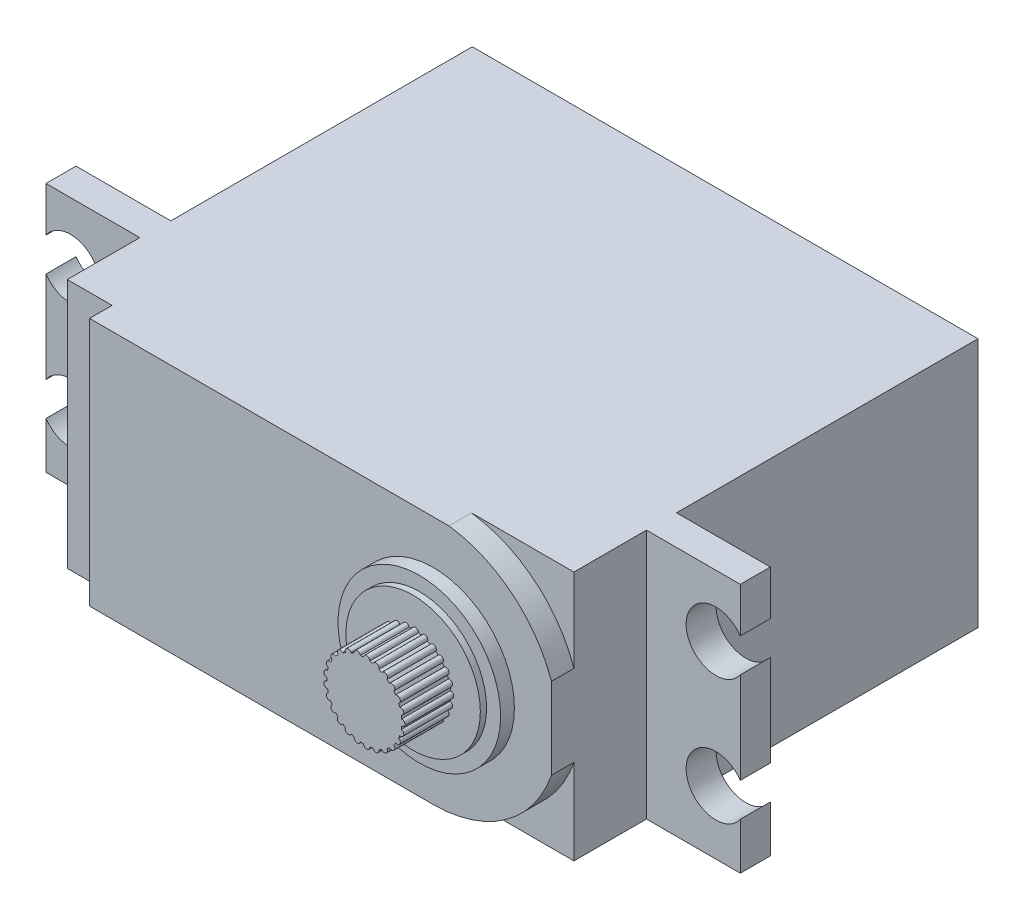
SolidWorks part; units mm, degrees
ref_plane "Ebene vorne" through (0, 0, 0) normal (0, 0, 1) x (1, 0, 0)
ref_plane "Ebene oben" through (0, 0, 0) normal (0, 1, 0) x (1, 0, 0)
ref_plane "Ebene rechts" through (0, 0, 0) normal (1, 0, 0) x (0, 0, -1)
sketch "Skizze1" plane through (0, 0, 0) normal (0, 0, 1) x (1, 0, 0)
  line L1 (0, 0) -> (55.5, 0)
  line L3 (0, -20) -> (55.5, -20)
  line L6 (0, 0) -> (62.9926, 0) construction
  line L7 (62.9926, 0) -> (27.75, 0) construction
  line L8 (27.75, 0) -> (27.75, 17.3109) construction
  line L9 (27.75, 17.3109) -> (27.75, -28.9374) construction
  line L12 (0, 0) -> (55.5, 0) construction
  line L13 (0, -3.5735) -> (0, 0) construction
  line L14 (0, 0) -> (55.5, 0) construction
  line L15 (55.5, 0) -> (55.5, -3.5735) construction
  line L16 (0, -16.266) -> (0, -20) construction
  line L17 (55.5, -6.266) -> (55.5, -13.5735) construction
  line L18 (0, -16.266) -> (0, -20)
  line L19 (0, -6.266) -> (0, -13.5735) construction
  line L20 (0, -3.5735) -> (0, 0)
  line L21 (55.5, 0) -> (55.5, -3.5735)
  line L22 (55.5, -6.266) -> (55.5, -13.5735)
  line L23 (0, -6.266) -> (0, -13.5735)
  line L24 (55.5, -16.266) -> (55.5, -20) construction
  line L25 (55.5, -16.266) -> (55.5, -20)
  arc A0 (0, -6.266) -> (0, -3.5735) centre (1.9566, -4.9197) ccw
  arc A4 (55.5, -6.266) -> (55.5, -3.5735) centre (53.5434, -4.9197) cw
  arc A5 (0, -16.266) -> (0, -13.5735) centre (1.9566, -14.9197) ccw
  arc A6 (55.5, -16.266) -> (55.5, -13.5735) centre (53.5434, -14.9197) cw
  dimension "D3" = 4.75
  dimension "D4" = 4.75
  dimension "D1" = 55.5
  dimension "D2" = 20
  dimension "D5" = 10
extrude "Aufsatz-Linear austragen1" add sketch "Skizze1" along normal blind 2.4
sketch "Skizze3" plane through (0, 0, 2.4) normal (0, 0, 1) x (1, 0, 0)
  line L0 (55.5, 0) -> (0, 0) construction
  line L1 (7.5, 0) -> (48, 0)
  line L2 (7.5, 0) -> (7.5, -20)
  line L3 (7.5, -20) -> (48, -20)
  line L4 (48, 0) -> (48, -20)
  line L5 (0, -20) -> (55.5, -20) construction
  dimension "D1" = 40.5
  dimension "D2" = 7.5
extrude "Aufsatz-Linear austragen2" add sketch "Skizze3" along normal blind 5.8
sketch "Skizze4" plane through (0, 0, 8.2) normal (0, 0, 1) x (1, 0, 0)
  line L0 (0, 0) -> (55.5, 0) construction
  line L1 (55.5, 0) -> (53.5434, -4.9197) construction
  line L2 (53.5434, -4.9197) -> (1.9566, -4.9197) construction
  line L4 (55.5, -13.5735) -> (55.5, -6.266) construction
  line L5 (55.5, -9.9197) -> (0, -9.9197) construction
  line L6 (0, -6.266) -> (0, -13.5735) construction
  line L7 (11.0819, 0) -> (38.5434, 0)
  line L8 (11.0819, 0) -> (11.0819, -19.9197)
  line L9 (11.0819, -19.9197) -> (38.5434, -19.9197)
  arc A0 (38.5434, -19.9197) -> (37.279, 0) centre (38.5434, -9.9197) ccw
  line M4 (48, -20) -> (48, 0)
  line M5 (48, 0) -> (7.5, 0)
  dimension "D1" = 20
  dimension "D2" = 15
extrude "Aufsatz-Linear austragen3" add sketch "Skizze4" along normal blind 1.8 contours A0 L7 L8 L9 M4 M5
sketch "Skizze5" plane through (0, 0, 10) normal (0, 0, 1) x (1, 0, 0)
  line L0 (0, 0) -> (55.5, 0) construction
  line L1 (0, -10) -> (38.5434, -10) construction
  line L2 (55.5, -20) -> (0, -20) construction
  line L3 (0, -20) -> (0, 0) construction
  line L4 (0, 0) -> (0, -10) construction
  line L5 (38.5434, -10) -> (55.5, -10) construction
  line L7 (53.5434, -4.9197) -> (38.5434, -4.9197) construction
  line L10 (38.5434, -9.9197) -> (38.5434, 2.8497) construction
  line L11 (38.5434, 2.8497) -> (38.5434, -23.2481) construction
  circle A0 centre (38.5434, -10) radius 6.5
  dimension "D1" = 13
extrude "Aufsatz-Linear austragen4" add sketch "Skizze5" along normal blind 1.1
sketch "Skizze7" plane through (0, 0, 11.1) normal (0, 0, 1) x (1, 0, 0)
  line L0 (48, 0) -> (48, -9.9197) construction
  line L1 (48, -13.1714) -> (48, -6.6681) construction
  line L2 (48, -9.9197) -> (0, -9.9197) construction
  line L3 (0, -6.266) -> (0, -13.5735) construction
  line L4 (48, -5.4374) -> (53.5434, -4.9197) construction
  line L5 (53.5434, -4.9197) -> (1.9566, -4.9197) construction
  line L6 (38.5434, -10) -> (38.5434, -22.4105) construction
  line L7 (38.5434, -22.4105) -> (38.5434, 3.8865) construction
  circle A0 centre (38.5434, -10) radius 5.375
  dimension "D1" = 10.75
extrude "Aufsatz-Linear austragen6" add sketch "Skizze7" along normal blind 0.5
sketch "Skizze8" plane through (0, 0, 11.6) normal (0, 0, 1) x (1, 0, 0)
  line L0 (55.5, 0) -> (55.5, -20) construction
  line L1 (55.5, -20) -> (55.5, -10) construction
  line L2 (55.5, -10) -> (41.7931, -9.9876) construction
  line L3 (11.0819, 0) -> (11.0819, -19.9197) construction
  line L4 (38.5434, -13) -> (38.5434, -21.6578) construction
  line L5 (53.5434, -4.9197) -> (11.0819, -4.9197) construction
  line L6 (38.5434, -21.6578) -> (38.5434, -13) construction
  line L7 (38.5434, -7) -> (38.5434, 1.1553) construction
  line L8 (35.5435, -9.982) -> (11.0819, -9.9599) construction
  line L9 (41.2938, -9.9872) -> (38.5434, -9.9847) construction
  arc A0 (41.377, -10.9854) -> (41.5012, -10.5015) centre (41.4492, -10.7461) ccw
  arc A1 (35.5461, -9.8731) -> (35.5461, -10.1269) centre (38.5434, -10) ccw
  arc A2 (41.533, -10.2498) -> (41.533, -9.7502) centre (41.5434, -10) ccw
  arc A3 (41.0429, -11.6591) -> (41.2836, -11.2214) centre (41.1724, -11.4453) ccw
  arc A4 (40.5518, -12.2286) -> (40.8937, -11.8644) centre (40.7303, -12.0536) ccw
  arc A5 (39.9344, -12.658) -> (40.3562, -12.3903) centre (40.1509, -12.533) ccw
  arc A6 (39.2297, -12.9204) -> (39.7048, -12.7661) centre (39.4705, -12.8532) ccw
  arc A7 (38.4819, -12.9994) -> (38.9804, -12.968) centre (38.7318, -12.9941) ccw
  arc A8 (37.7379, -12.8898) -> (38.2286, -12.9834) centre (37.9813, -12.9469) ccw
  arc A9 (37.0445, -12.5987) -> (37.4965, -12.8114) centre (37.2661, -12.7145) ccw
  arc A10 (36.4453, -12.1443) -> (36.8303, -12.4627) centre (36.6312, -12.3115) ccw
  arc A11 (35.978, -11.5552) -> (36.2716, -11.9593) centre (36.1164, -11.7634) ccw
  arc A12 (35.6718, -10.8683) -> (35.8557, -11.3328) centre (35.7541, -11.1044) ccw
  arc A13 (35.5461, -10.1269) -> (35.6087, -10.6225) centre (35.5671, -10.376) ccw
  arc A14 (35.6087, -9.3775) -> (35.5461, -9.8731) centre (35.5671, -9.624) ccw
  arc A15 (35.8557, -8.6672) -> (35.6718, -9.1317) centre (35.7541, -8.8956) ccw
  arc A16 (36.2716, -8.0407) -> (35.978, -8.4448) centre (36.1164, -8.2366) ccw
  arc A17 (36.8303, -7.5373) -> (36.4453, -7.8557) centre (36.6312, -7.6885) ccw
  arc A18 (37.4965, -7.1886) -> (37.0445, -7.4013) centre (37.2661, -7.2855) ccw
  arc A19 (38.2286, -7.0166) -> (37.7379, -7.1102) centre (37.9813, -7.0531) ccw
  arc A20 (38.9804, -7.032) -> (38.4819, -7.0006) centre (38.7318, -7.0059) ccw
  arc A21 (39.7048, -7.2339) -> (39.2297, -7.0796) centre (39.4705, -7.1468) ccw
  arc A22 (40.3562, -7.6097) -> (39.9344, -7.342) centre (40.1509, -7.467) ccw
  arc A23 (40.8937, -8.1356) -> (40.5518, -7.7714) centre (40.7303, -7.9464) ccw
  arc A24 (41.2836, -8.7786) -> (41.0429, -8.3409) centre (41.1724, -8.5547) ccw
  arc A25 (41.5012, -9.4985) -> (41.377, -9.0146) centre (41.4492, -9.2539) ccw
  arc A26 (35.6087, -10.6225) -> (35.6718, -10.8683) centre (38.5434, -10) ccw
  arc A27 (35.8557, -11.3328) -> (35.978, -11.5552) centre (38.5434, -10) ccw
  arc A28 (36.2716, -11.9593) -> (36.4453, -12.1443) centre (38.5434, -10) ccw
  arc A29 (36.8303, -12.4627) -> (37.0445, -12.5987) centre (38.5434, -10) ccw
  arc A30 (37.4965, -12.8114) -> (37.7379, -12.8898) centre (38.5434, -10) ccw
  arc A31 (38.2286, -12.9834) -> (38.5434, -13) centre (38.5434, -10) ccw
  arc A32 (38.9804, -12.968) -> (39.2297, -12.9204) centre (38.5434, -10) ccw
  arc A33 (39.7048, -12.7661) -> (39.9344, -12.658) centre (38.5434, -10) ccw
  arc A34 (40.3562, -12.3903) -> (40.5518, -12.2286) centre (38.5434, -10) ccw
  arc A35 (41.2836, -11.2214) -> (41.377, -10.9854) centre (38.5434, -10) ccw
  arc A36 (40.8937, -11.8644) -> (41.0429, -11.6591) centre (38.5434, -10) ccw
  arc A37 (41.5012, -10.5015) -> (41.533, -10.2498) centre (38.5434, -10) ccw
  arc A38 (41.533, -9.7502) -> (41.5012, -9.4985) centre (38.5434, -10) ccw
  arc A39 (41.377, -9.0146) -> (41.2836, -8.7786) centre (38.5434, -10) ccw
  arc A40 (41.0429, -8.3409) -> (40.8937, -8.1356) centre (38.5434, -10) ccw
  arc A41 (40.5518, -7.7714) -> (40.3562, -7.6097) centre (38.5434, -10) ccw
  arc A42 (39.9344, -7.342) -> (39.7048, -7.2339) centre (38.5434, -10) ccw
  arc A43 (39.2297, -7.0796) -> (38.9804, -7.032) centre (38.5434, -10) ccw
  arc A44 (38.4819, -7.0006) -> (38.2286, -7.0166) centre (38.5434, -10) ccw
  arc A45 (37.7379, -7.1102) -> (37.4965, -7.1886) centre (38.5434, -10) ccw
  arc A46 (37.0445, -7.4013) -> (36.8303, -7.5373) centre (38.5434, -10) ccw
  arc A47 (36.4453, -7.8557) -> (36.2716, -8.0407) centre (38.5434, -10) ccw
  arc A48 (35.978, -8.4448) -> (35.8557, -8.6672) centre (38.5434, -10) ccw
  arc A49 (35.6718, -9.1317) -> (35.6087, -9.3775) centre (38.5434, -10) ccw
  point P69 (38.5434, -10)
  dimension "D1" = 6
  dimension "D2" = 0.5
  dimension "D3" = 25
extrude "Aufsatz-Linear austragen7" add sketch "Skizze8" along normal blind 3.9
sketch "Skizze9" plane through (0, 0, 0) normal (0, 1, 0) x (1, 0, 0)
  line L0 (48, 0) -> (48, 20.2658) construction
  line L1 (48, 0) -> (7.5762, 0) construction
  line L3 (48, 0) -> (7.5762, 0)
  line L5 (48, 0) -> (48, 24.1)
  line L6 (48, 24.1) -> (7.5762, 24.1)
  line L7 (7.5762, 0) -> (7.5762, 24.1)
extrude "Aufsatz-Linear austragen8" add sketch "Skizze9" against normal blind 20
